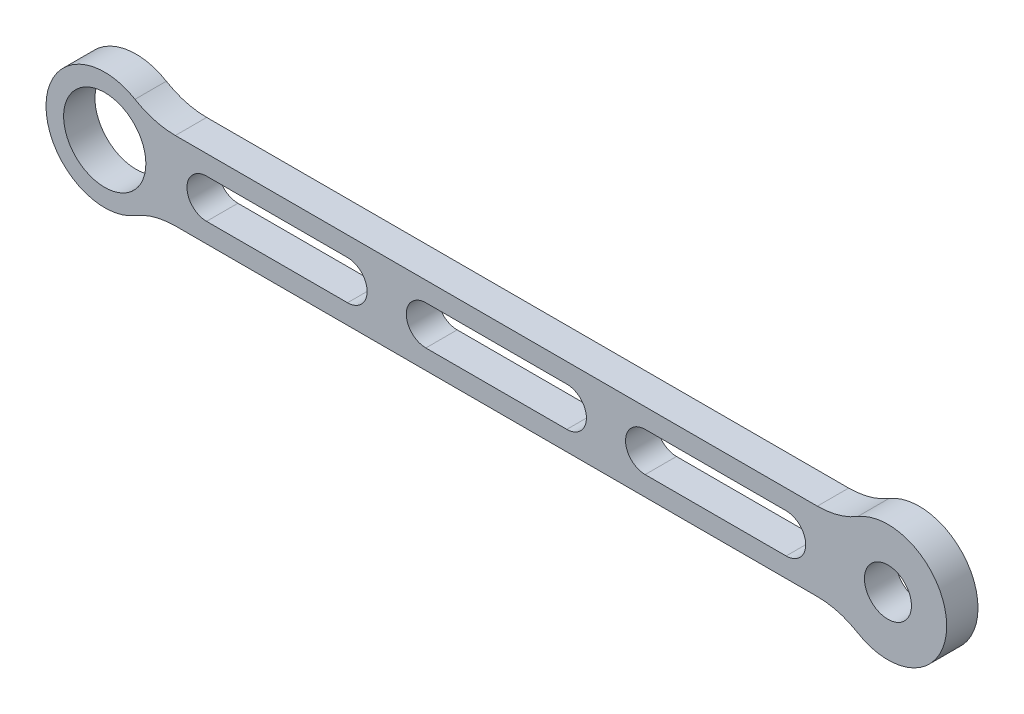
SolidWorks part; units mm, degrees
material "7075-T6，板材(SS)"
ref_plane "前视基准面" through (0, 0, 0) normal (0, 0, 1) x (1, 0, 0)
ref_plane "上视基准面" through (0, 0, 0) normal (0, 1, 0) x (1, 0, 0)
ref_plane "右视基准面" through (0, 0, 0) normal (1, 0, 0) x (0, 0, -1)
sketch "草图1" plane through (0, 0, 0) normal (0, 0, 1) x (1, 0, 0)
  line L0 (0, 0) -> (200, 0) construction
  line L1 (0, 0) -> (0, 10) construction
  line L6 (0, 10) -> (200, 10)
  line L7 (0, 10) -> (0, -10)
  line L8 (0, -10) -> (200, -10)
  line L9 (200, 10) -> (200, -10)
  circle A1 centre (200, 0) radius 15
  circle A2 centre (0, 0) radius 15
  dimension "D1" = 30
  dimension "D3" = 30
  dimension "D2" = 200
  dimension "D4" = 10
  dimension "D5" = 20
  dimension "D6" = 200
extrude "凸台-拉伸1" add sketch "草图1" along normal blind 8 contours L6 A2 L8 L7 | L8 A2 L6 L7 | A2 L8 A1 L6 | L8 A1 L6 L9 | L6 A1 L8 L9
fillet "圆角1" radius 20 4 edges at (188.8197, 10, 4) (188.8197, -10, 4) (11.1803, -10, 4) (11.1803, 10, 4)
sketch "草图5" plane through (0, 0, 8) normal (0, 0, 1) x (1, 0, 0)
  circle A0 centre (0, 0) radius 10.5
  circle A1 centre (200, 0) radius 6
  dimension "D1" = 21
  dimension "D2" = 12
extrude "切除-拉伸4" cut sketch "草图5" against normal blind 10
sketch "草图6" plane through (0, 0, 8) normal (0, 0, 1) x (1, 0, 0)
  line L0 (100, 10) -> (100, -10) construction
  line L3 (18.0278, 10) -> (181.9722, 10) construction
  line L8 (18.0278, -10) -> (181.9722, -10) construction
  line L19 (138, -5) -> (174, -5)
  line L20 (82, -5) -> (118, -5)
  line L21 (82, -5) -> (82, 5)
  line L24 (82, 5) -> (118, 5)
  line L25 (118, -5) -> (118, 5)
  line L26 (82, -5) -> (118, 5) construction
  line L27 (82, 5) -> (118, -5) construction
  line L28 (138, -5) -> (138, 5)
  line L29 (138, 5) -> (174, 5)
  line L30 (174, -5) -> (174, 5)
  line L31 (156, 10) -> (156, -10) construction
  line L32 (138, -5) -> (174, 5) construction
  line L33 (138, 5) -> (174, -5) construction
  line L34 (26, -5) -> (62, -5)
  line L35 (26, -5) -> (26, 5)
  line L36 (26, 5) -> (62, 5)
  line L37 (62, -5) -> (62, 5)
  line L38 (44, 10) -> (44, -10) construction
  line L39 (26, -5) -> (62, 5) construction
  line L40 (26, 5) -> (62, -5) construction
  circle A9 centre (82, 0) radius 5
  circle A10 centre (118, 0) radius 5
  circle A11 centre (138, 0) radius 5
  circle A12 centre (174, 0) radius 5
  circle A13 centre (26, 0) radius 5
  circle A14 centre (62, 0) radius 5
  point P6 (100, 0)
  point P19 (156, 0)
  point P30 (44, 0)
  dimension "D3" = 10
  dimension "D1" = 10
  dimension "D2" = 36
extrude "切除-拉伸5" cut sketch "草图6" against normal blind 10 contours A14 L36 A13 L34 | L35 A13 | L35 A13 | L37 A14 | L37 A14 | L21 A9 | L21 A9 | A10 L24 A9 L20 | L25 A10 | L25 A10 | L28 A11 | L28 A11 | A12 L29 A11 L19 | L30 A12 | L30 A12
